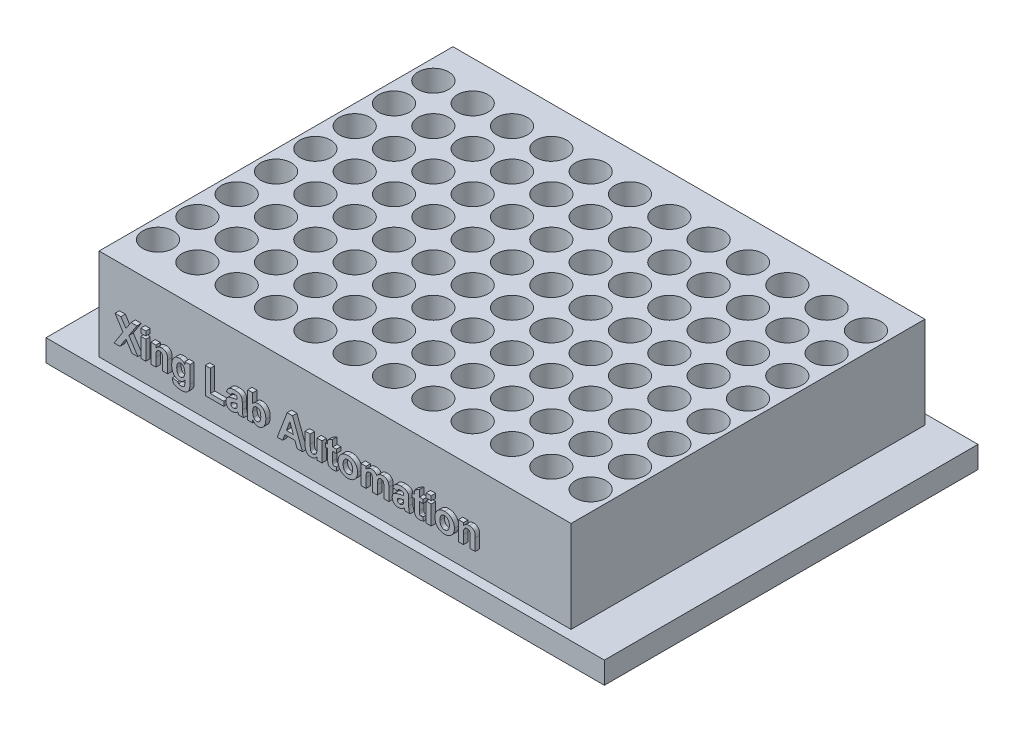
SolidWorks part; units mm, degrees
ref_plane "前视基准面" through (0, 0, 0) normal (0, 0, 1) x (1, 0, 0)
ref_plane "上视基准面" through (0, 0, 0) normal (0, 1, 0) x (1, 0, 0)
ref_plane "右视基准面" through (0, 0, 0) normal (1, 0, 0) x (0, 0, -1)
other "Configuration Table"
sketch "草图1" plane through (0, 0, 0) normal (0, 1, 0) x (1, 0, 0)
  line L1 (-63.885, 42.75) -> (63.885, 42.75)
  line L2 (-63.885, 42.75) -> (-63.885, -42.75)
  line L3 (-63.885, -42.75) -> (63.885, -42.75)
  line L4 (63.885, 42.75) -> (63.885, -42.75)
  line L5 (-63.885, 42.75) -> (63.885, -42.75) construction
  line L6 (-63.885, -42.75) -> (63.885, 42.75) construction
  point P0 (0, 0)
  dimension "D1" = 127.77
  dimension "D2" = 85.5
extrude "凸台-拉伸1" add sketch "草图1" along normal blind 5
sketch "草图2" plane through (0, 5, 0) normal (0, 1, 0) x (1, 0, 0)
  line L0 (49.5, 31.5) -> (40.5, 31.5) construction
  line L1 (-54, 40.485) -> (54, 40.485)
  line L2 (-54, 40.485) -> (-54, -40.485)
  line L3 (-54, -40.485) -> (54, -40.485)
  line L4 (54, 40.485) -> (54, -40.485)
  line L5 (-54, 40.485) -> (54, -40.485) construction
  line L6 (-54, -40.485) -> (54, 40.485) construction
  circle A0 centre (49.5, 31.5) radius 3.5
  circle A1 centre (40.5, 31.5) radius 3.5
  circle A2 centre (31.5, 31.5) radius 3.5
  circle A3 centre (22.5, 31.5) radius 3.5
  circle A4 centre (13.5, 31.5) radius 3.5
  circle A5 centre (4.5, 31.5) radius 3.5
  circle A6 centre (-4.5, 31.5) radius 3.5
  circle A7 centre (-13.5, 31.5) radius 3.5
  circle A8 centre (-22.5, 31.5) radius 3.5
  circle A9 centre (-31.5, 31.5) radius 3.5
  circle A10 centre (-40.5, 31.5) radius 3.5
  circle A11 centre (-49.5, 31.5) radius 3.5
  circle A12 centre (40.5, 22.5) radius 3.5
  circle A13 centre (31.5, 22.5) radius 3.5
  circle A14 centre (22.5, 22.5) radius 3.5
  circle A15 centre (13.5, 22.5) radius 3.5
  circle A16 centre (4.5, 22.5) radius 3.5
  circle A17 centre (-4.5, 22.5) radius 3.5
  circle A18 centre (-13.5, 22.5) radius 3.5
  circle A19 centre (-22.5, 22.5) radius 3.5
  circle A20 centre (-31.5, 22.5) radius 3.5
  circle A21 centre (-40.5, 22.5) radius 3.5
  circle A22 centre (-49.5, 22.5) radius 3.5
  circle A23 centre (40.5, 13.5) radius 3.5
  circle A24 centre (31.5, 13.5) radius 3.5
  circle A25 centre (22.5, 13.5) radius 3.5
  circle A26 centre (13.5, 13.5) radius 3.5
  circle A27 centre (4.5, 13.5) radius 3.5
  circle A28 centre (-4.5, 13.5) radius 3.5
  circle A29 centre (-13.5, 13.5) radius 3.5
  circle A30 centre (-22.5, 13.5) radius 3.5
  circle A31 centre (-31.5, 13.5) radius 3.5
  circle A32 centre (-40.5, 13.5) radius 3.5
  circle A33 centre (-49.5, 13.5) radius 3.5
  circle A34 centre (40.5, 4.5) radius 3.5
  circle A35 centre (31.5, 4.5) radius 3.5
  circle A36 centre (22.5, 4.5) radius 3.5
  circle A37 centre (13.5, 4.5) radius 3.5
  circle A38 centre (4.5, 4.5) radius 3.5
  circle A39 centre (-4.5, 4.5) radius 3.5
  circle A40 centre (-13.5, 4.5) radius 3.5
  circle A41 centre (-22.5, 4.5) radius 3.5
  circle A42 centre (-31.5, 4.5) radius 3.5
  circle A43 centre (-40.5, 4.5) radius 3.5
  circle A44 centre (-49.5, 4.5) radius 3.5
  circle A45 centre (40.5, -4.5) radius 3.5
  circle A46 centre (31.5, -4.5) radius 3.5
  circle A47 centre (22.5, -4.5) radius 3.5
  circle A48 centre (13.5, -4.5) radius 3.5
  circle A49 centre (4.5, -4.5) radius 3.5
  circle A50 centre (-4.5, -4.5) radius 3.5
  circle A51 centre (-13.5, -4.5) radius 3.5
  circle A52 centre (-22.5, -4.5) radius 3.5
  circle A53 centre (-31.5, -4.5) radius 3.5
  circle A54 centre (-40.5, -4.5) radius 3.5
  circle A55 centre (-49.5, -4.5) radius 3.5
  circle A56 centre (40.5, -13.5) radius 3.5
  circle A57 centre (31.5, -13.5) radius 3.5
  circle A58 centre (22.5, -13.5) radius 3.5
  circle A59 centre (13.5, -13.5) radius 3.5
  circle A60 centre (4.5, -13.5) radius 3.5
  circle A61 centre (-4.5, -13.5) radius 3.5
  circle A62 centre (-13.5, -13.5) radius 3.5
  circle A63 centre (-22.5, -13.5) radius 3.5
  circle A64 centre (-31.5, -13.5) radius 3.5
  circle A65 centre (-40.5, -13.5) radius 3.5
  circle A66 centre (-49.5, -13.5) radius 3.5
  circle A67 centre (40.5, -22.5) radius 3.5
  circle A68 centre (31.5, -22.5) radius 3.5
  circle A69 centre (22.5, -22.5) radius 3.5
  circle A70 centre (13.5, -22.5) radius 3.5
  circle A71 centre (4.5, -22.5) radius 3.5
  circle A72 centre (-4.5, -22.5) radius 3.5
  circle A73 centre (-13.5, -22.5) radius 3.5
  circle A74 centre (-22.5, -22.5) radius 3.5
  circle A75 centre (-31.5, -22.5) radius 3.5
  circle A76 centre (-40.5, -22.5) radius 3.5
  circle A77 centre (-49.5, -22.5) radius 3.5
  circle A78 centre (40.5, -31.5) radius 3.5
  circle A79 centre (31.5, -31.5) radius 3.5
  circle A80 centre (22.5, -31.5) radius 3.5
  circle A81 centre (13.5, -31.5) radius 3.5
  circle A82 centre (4.5, -31.5) radius 3.5
  circle A83 centre (-4.5, -31.5) radius 3.5
  circle A84 centre (-13.5, -31.5) radius 3.5
  circle A85 centre (-22.5, -31.5) radius 3.5
  circle A86 centre (-31.5, -31.5) radius 3.5
  circle A87 centre (-40.5, -31.5) radius 3.5
  circle A88 centre (-49.5, -31.5) radius 3.5
  circle A89 centre (49.5, 22.5) radius 3.5
  circle A90 centre (49.5, 13.5) radius 3.5
  circle A91 centre (49.5, 4.5) radius 3.5
  circle A92 centre (49.5, -4.5) radius 3.5
  circle A93 centre (49.5, -13.5) radius 3.5
  circle A94 centre (49.5, -22.5) radius 3.5
  circle A95 centre (49.5, -31.5) radius 3.5
  point P0 (0, 0)
  dimension "D2" = 12
  dimension "D5" = 7
  dimension "D1" = 80.97
  dimension "121.26" = 108
  dimension "D4" = 9
  dimension "D3" = 8
extrude "凸台-拉伸6" add sketch "草图2" along normal blind 21
sketch "草图4" plane through (0, 0, 40.485) normal (0, 0, 1) x (1, 0, 0)
  text T0 "<b>Xing Lab Automation</b>" font "Helvetica" height 6
extrude "凸台-拉伸8" add sketch "草图4" along normal blind 1
